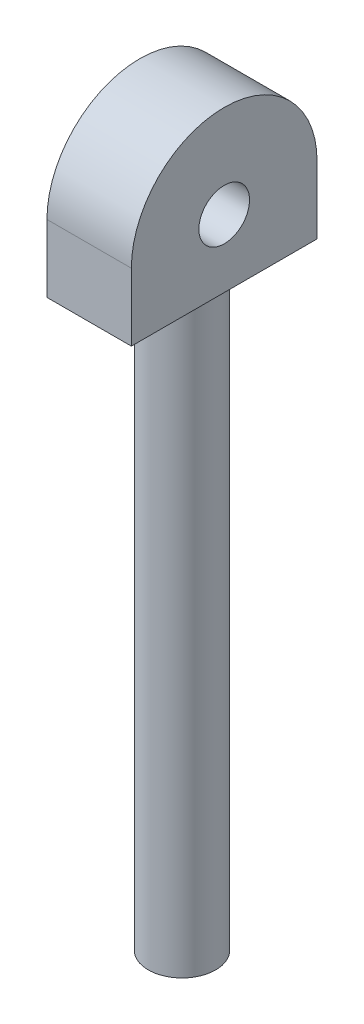
SolidWorks part; units mm, degrees
ref_plane "Front" through (0, 0, 0) normal (0, 0, 1) x (1, 0, 0)
ref_plane "Top" through (0, 0, 0) normal (0, 1, 0) x (1, 0, 0)
ref_plane "Right" through (0, 0, 0) normal (1, 0, 0) x (0, 0, -1)
sketch "Sketch1" plane through (0, 0, 0) normal (1, 0, 0) x (0, 0, -1)
  line L0 (0, 2) -> (0, -2) construction
  line L1 (-5.5, 2) -> (-5.5, -2)
  line L2 (5.5, 2) -> (5.5, -2)
  line L5 (-5.5, -2) -> (5.5, -2)
  circle A0 centre (0, 2) radius 1.5
  arc A6 (5.5, 2) -> (-5.5, 2) centre (0, 2) ccw
  point P3 (0, 0)
  point P10 (0, 0)
  dimension "D4" = 3
  dimension "D2" = 4
  dimension "D1" = 4
extrude "Boss-Extrude1" add sketch "Sketch1" along normal blind 5
sketch "Sketch2" plane through (0, -2, 0) normal (0, -1, 0) x (1, 0, 0)
  line L0 (2.5, 5.5) -> (2.5, -5.5) construction
  line L4 (5, 5.5) -> (0, 5.5) construction
  circle A0 centre (2.5, 0) radius 2
  point P2 (0, 0)
  point P4 (0, 0)
  point P8 (0, 0)
  point P12 (2.5, -3.7749)
  point P13 (2.5, 5.5)
  dimension "D1" = 4
extrude "Boss-Extrude2" add sketch "Sketch2" along normal blind 35
